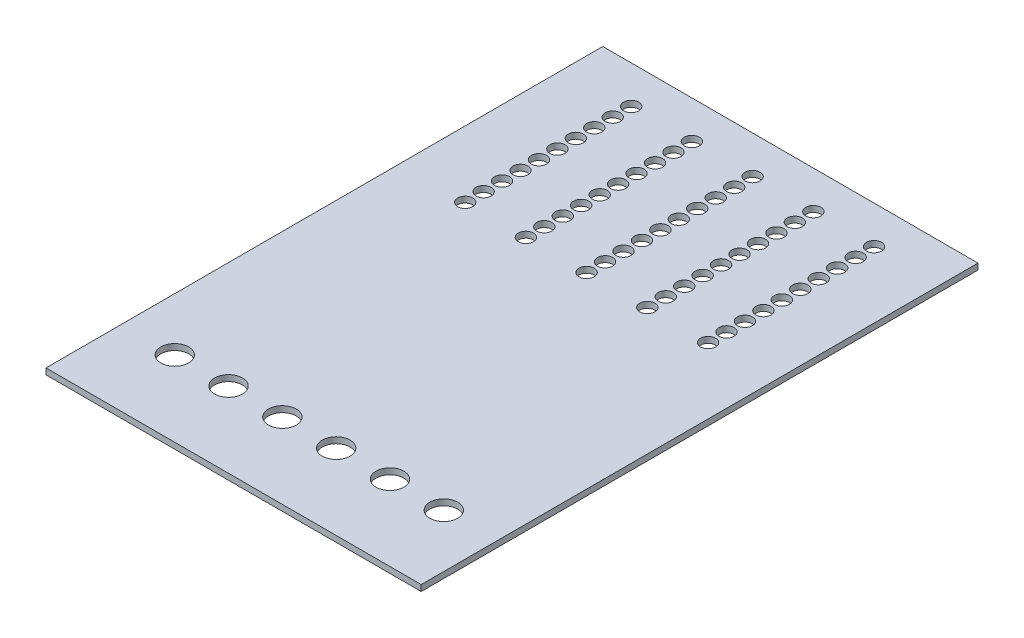
SolidWorks part; units mm, degrees
ref_plane "Front Plane" through (0, 0, 0) normal (0, 0, 1) x (1, 0, 0)
ref_plane "Top Plane" through (0, 0, 0) normal (0, 1, 0) x (1, 0, 0)
ref_plane "Right Plane" through (0, 0, 0) normal (1, 0, 0) x (0, 0, -1)
sketch "Sketch1" plane through (0, 60, 0) normal (0, 1, 0) x (1, 0, 0)
  line L0 (-40.132, 79.5172) -> (-20.066, 79.5172) construction
  line L1 (-62, 92) -> (62, 92)
  line L2 (-62, 92) -> (-62, -92)
  line L3 (-62, -92) -> (62, -92)
  line L4 (62, 92) -> (62, -92)
  circle A0 centre (-40.132, 79.5172) radius 2.5
  circle A1 centre (-20.066, 79.5172) radius 2.5
  circle A2 centre (0, 79.5172) radius 2.5
  circle A3 centre (20.066, 79.5172) radius 2.5
  circle A4 centre (40.132, 79.5172) radius 2.5
  circle A5 centre (-20.066, 73.4212) radius 2.5
  circle A6 centre (0, 73.4212) radius 2.5
  circle A7 centre (20.066, 73.4212) radius 2.5
  circle A8 centre (40.132, 73.4212) radius 2.5
  circle A9 centre (-20.066, 67.3252) radius 2.5
  circle A10 centre (0, 67.3252) radius 2.5
  circle A11 centre (20.066, 67.3252) radius 2.5
  circle A12 centre (40.132, 67.3252) radius 2.5
  circle A13 centre (-20.066, 61.2292) radius 2.5
  circle A14 centre (0, 61.2292) radius 2.5
  circle A15 centre (20.066, 61.2292) radius 2.5
  circle A16 centre (40.132, 61.2292) radius 2.5
  circle A17 centre (-20.066, 55.1332) radius 2.5
  circle A18 centre (0, 55.1332) radius 2.5
  circle A19 centre (20.066, 55.1332) radius 2.5
  circle A20 centre (40.132, 55.1332) radius 2.5
  circle A21 centre (-20.066, 49.0372) radius 2.5
  circle A22 centre (0, 49.0372) radius 2.5
  circle A23 centre (20.066, 49.0372) radius 2.5
  circle A24 centre (40.132, 49.0372) radius 2.5
  circle A25 centre (-20.066, 42.9412) radius 2.5
  circle A26 centre (0, 42.9412) radius 2.5
  circle A27 centre (20.066, 42.9412) radius 2.5
  circle A28 centre (40.132, 42.9412) radius 2.5
  circle A29 centre (-20.066, 36.8452) radius 2.5
  circle A30 centre (0, 36.8452) radius 2.5
  circle A31 centre (20.066, 36.8452) radius 2.5
  circle A32 centre (40.132, 36.8452) radius 2.5
  circle A33 centre (-20.066, 30.7492) radius 2.5
  circle A34 centre (0, 30.7492) radius 2.5
  circle A35 centre (20.066, 30.7492) radius 2.5
  circle A36 centre (40.132, 30.7492) radius 2.5
  circle A37 centre (-20.066, 24.6532) radius 2.5
  circle A38 centre (0, 24.6532) radius 2.5
  circle A39 centre (20.066, 24.6532) radius 2.5
  circle A40 centre (40.132, 24.6532) radius 2.5
  circle A41 centre (-40.132, 73.4212) radius 2.5
  circle A42 centre (-40.132, 67.3252) radius 2.5
  circle A43 centre (-40.132, 61.2292) radius 2.5
  circle A44 centre (-40.132, 55.1332) radius 2.5
  circle A45 centre (-40.132, 49.0372) radius 2.5
  circle A46 centre (-40.132, 42.9412) radius 2.5
  circle A47 centre (-40.132, 36.8452) radius 2.5
  circle A48 centre (-40.132, 30.7492) radius 2.5
  circle A49 centre (-40.132, 24.6532) radius 2.5
  dimension "D1" = 2.5
  dimension "D2" = 10
  dimension "D3" = 20.066
extrude "Boss-Extrude1" add sketch "Sketch1" along normal blind 2
sketch "Sketch5" plane through (0, 62, 0) normal (0, 1, 0) x (1, 0, 0)
  line L0 (-44.45, -67) -> (-26.67, -67) construction
  line L1 (-44.45, -67) -> (44.45, -67) construction
  line L2 (-62, -92) -> (62, -92) construction
  circle A0 centre (-44.45, -67) radius 4.6
  circle A1 centre (-26.67, -67) radius 4.6
  circle A2 centre (-8.89, -67) radius 4.6
  circle A3 centre (8.89, -67) radius 4.6
  circle A4 centre (26.67, -67) radius 4.6
  circle A5 centre (44.45, -67) radius 4.6
  point P12 (0, -67)
  dimension "D1" = 4.6
  dimension "D2" = 17.78
  dimension "D3" = 25
extrude "Cut-Extrude2" cut sketch "Sketch5" against normal up to next
